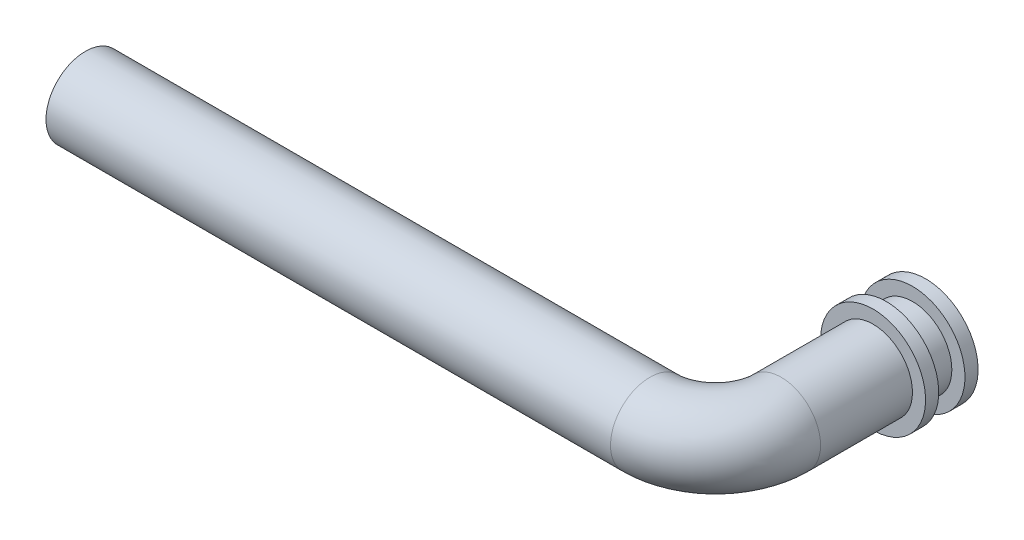
SolidWorks part; units mm, degrees
ref_plane "Front Plane" through (0, 0, 0) normal (0, 0, 1) x (1, 0, 0)
ref_plane "Top Plane" through (0, 0, 0) normal (0, 1, 0) x (1, 0, 0)
ref_plane "Right Plane" through (0, 0, 0) normal (1, 0, 0) x (0, 0, -1)
sketch "Sketch2" plane through (0, 0, 0) normal (0, 0, 1) x (1, 0, 0)
  circle A0 centre (0, 0) radius 6
  dimension "D1" = 12
sketch3d "3DSketch3"
  line L0 (0, 0, 0) -> (0, 0, 20)
  line L1 (-10, 0, 30) -> (-96, 0, 30)
  arc A0 (-10, 0, 30) -> (0, 0, 20) centre (-10, 0, 20) ccw
  point P6 (0, 0, 30)
  point P7 (-10, 10, 20)
  dimension "D1" = 10
  dimension "D2" = 30
  dimension "D3" = 96
sweep "Sweep1" add profiles "Sketch2" path "3DSketch3"
sketch "Sketch4" plane through (0, 0, 0) normal (0, 0, -1) x (-1, 0, 0)
  circle A0 centre (0, 0) radius 8
  dimension "D1" = 16
extrude "Boss-Extrude1" add sketch "Sketch4" along normal blind 2
ref_plane "Plane1" through (0, 0, 6) normal (0, 0, -1) x (-1, 0, 0)
sketch "Sketch5" plane through (0, 0, 6) normal (0, 0, -1) x (-1, 0, 0)
  circle A2 centre (0, 0) radius 8
  circle A3 centre (0, 0) radius 6 construction
  circle A4 centre (0, 0) radius 6
  dimension "D1" = 16
extrude "Boss-Extrude2" add sketch "Sketch5" along normal blind 2
